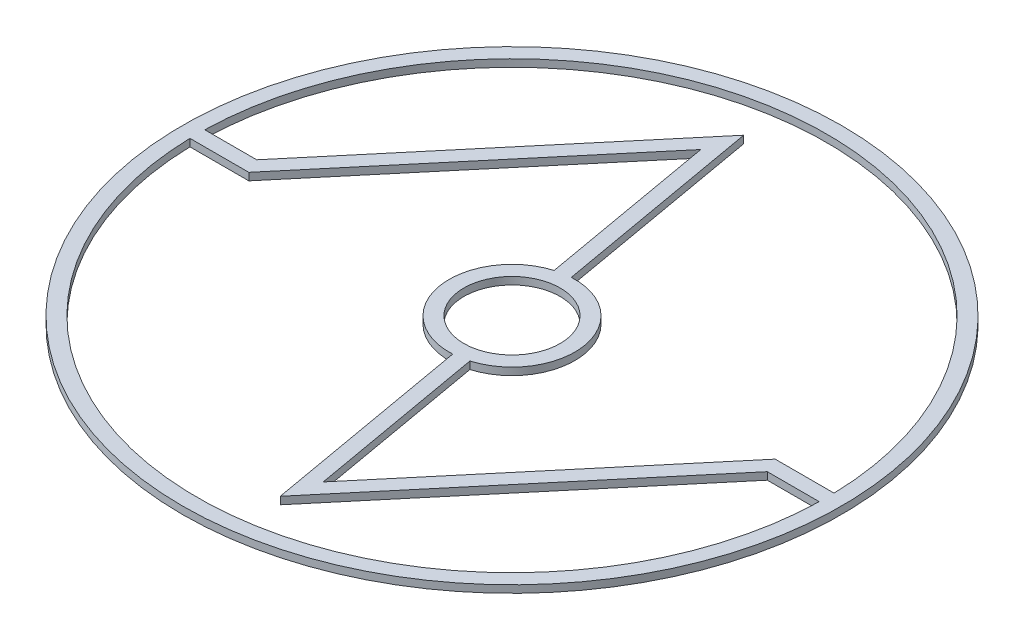
SolidWorks part; units mm, degrees
ref_plane "Спереди" through (0, 0, 0) normal (0, 0, 1) x (1, 0, 0)
ref_plane "Сверху" through (0, 0, 0) normal (0, 1, 0) x (1, 0, 0)
ref_plane "Справа" through (0, 0, 0) normal (1, 0, 0) x (0, 0, -1)
sketch "Эскиз1" plane through (0, 0, 0) normal (0, 1, 0) x (1, 0, 0)
  line L0 (-42.5, 0) -> (-35.0038, 0) construction
  line L1 (-35.0038, 0) -> (-6.0783, 34.472) construction
  line L2 (-6.0783, 34.472) -> (6.0783, -34.472) construction
  line L3 (6.0783, -34.472) -> (35.0038, 0) construction
  line L4 (35.0038, 0) -> (42.5, 0) construction
  line L5 (-42.4882, 1) -> (-35.4701, 1)
  line L6 (-35.4701, 1) -> (-5.4659, 36.7576)
  line L7 (-5.4659, 36.7576) -> (6.6908, -32.1864)
  line L8 (6.6908, -32.1864) -> (34.5375, 1)
  line L9 (34.5375, 1) -> (42.4882, 1)
  line L11 (42.4882, -1) -> (35.4701, -1)
  line L12 (35.4701, -1) -> (5.4659, -36.7576)
  line L13 (5.4659, -36.7576) -> (-6.6908, 32.1864)
  line L14 (-6.6908, 32.1864) -> (-34.5375, -1)
  line L15 (-34.5375, -1) -> (-42.4882, -1)
  circle A0 centre (0, 0) radius 44.5
  circle A1 centre (0, 0) radius 42.5
  circle A4 centre (0, 0) radius 8.5
  circle A5 centre (0, 0) radius 6.5
  dimension "D1" = 89
  dimension "D2" = 2
  dimension "D12" = 2
  dimension "D13" = 13
  dimension "D3" = 50
  dimension "D4" = 45
  dimension "D5" = 2
  dimension "D6" = 1
  dimension "D7" = 2
  dimension "D8" = 2
  dimension "D9" = 2
  dimension "D10" = 2
  dimension "D11" = 130
extrude "Бобышка-Вытянуть7" add sketch "Эскиз1" along normal blind 1 contours A0 A1 | A4 L7 L6 L5 A1 L15 L14 L13 | A5 L7 A4 | A5 L7 A4 L13 | A5 L13 A4 | A4 L13 L12 L11 A1 L9 L8 L7 | A5 L13 A4 L7
